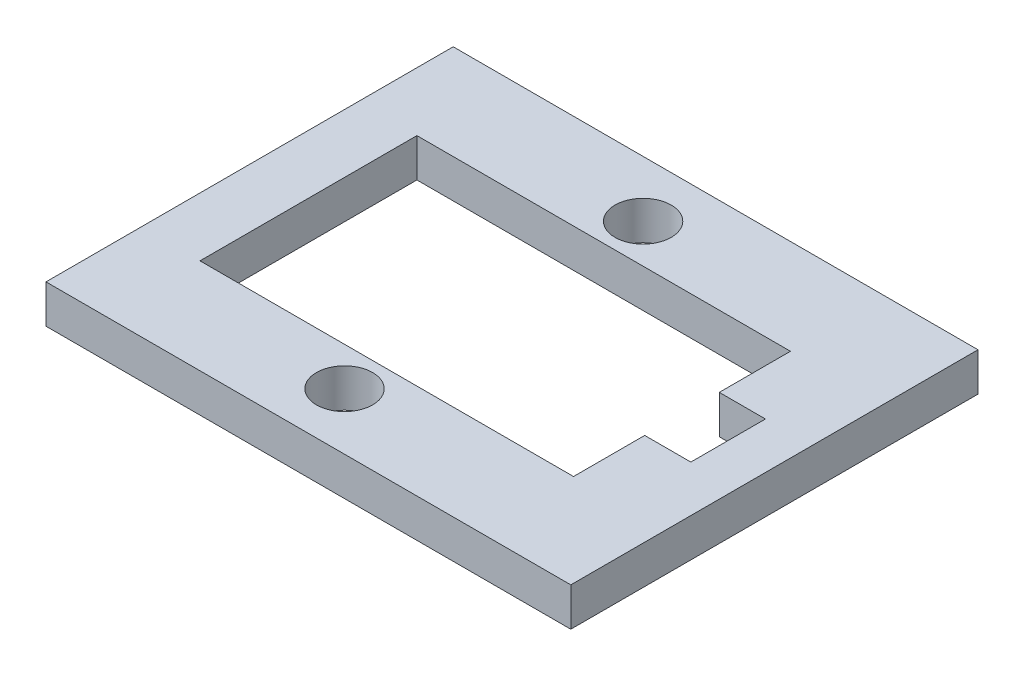
SolidWorks part; units mm, degrees
ref_plane "Front Plane" through (0, 0, 0) normal (0, 0, 1) x (1, 0, 0)
ref_plane "Top Plane" through (0, 0, 0) normal (0, 1, 0) x (1, 0, 0)
ref_plane "Right Plane" through (0, 0, 0) normal (1, 0, 0) x (0, 0, -1)
sketch "Sketch2" plane through (0, 0, 0) normal (0, 1, 0) x (1, 0, 0)
  line L0 (-12.8784, 7.8335) -> (11.4112, 7.8335)
  line L1 (-16.7015, 14.0166) -> (17.4229, 14.0166)
  line L2 (-16.7015, 14.0166) -> (-16.7015, -12.4616)
  line L3 (-16.7015, -12.4616) -> (17.4229, -12.4616)
  line L4 (17.4229, 14.0166) -> (17.4229, -12.4616)
  line L5 (11.4112, 7.8335) -> (11.4112, 3.2059)
  line L6 (11.4112, 3.2059) -> (14.4112, 3.2059)
  line L7 (14.4112, 3.2059) -> (14.4112, -1.6439)
  line L8 (14.4112, -1.6439) -> (11.4112, -1.6439)
  line L9 (11.4112, -1.6439) -> (11.4112, -6.2716)
  line L10 (11.4112, -6.2716) -> (-12.8784, -6.2716)
  line L11 (-12.8784, -6.2716) -> (-12.8784, 7.8335)
  circle A0 centre (-0.7026, 10.3665) radius 1.825
  circle A1 centre (-0.978, -8.7735) radius 1.825
  dimension "D8" = 3.65
  dimension "D1" = 19.14
  dimension "D2" = 26.4782
  dimension "D3" = 4.6277
  dimension "D4" = 24.2896
  dimension "D5" = 3
  dimension "D6" = 4.8498
extrude "Boss-Extrude1" add sketch "Sketch2" along normal mid plane 2.5
